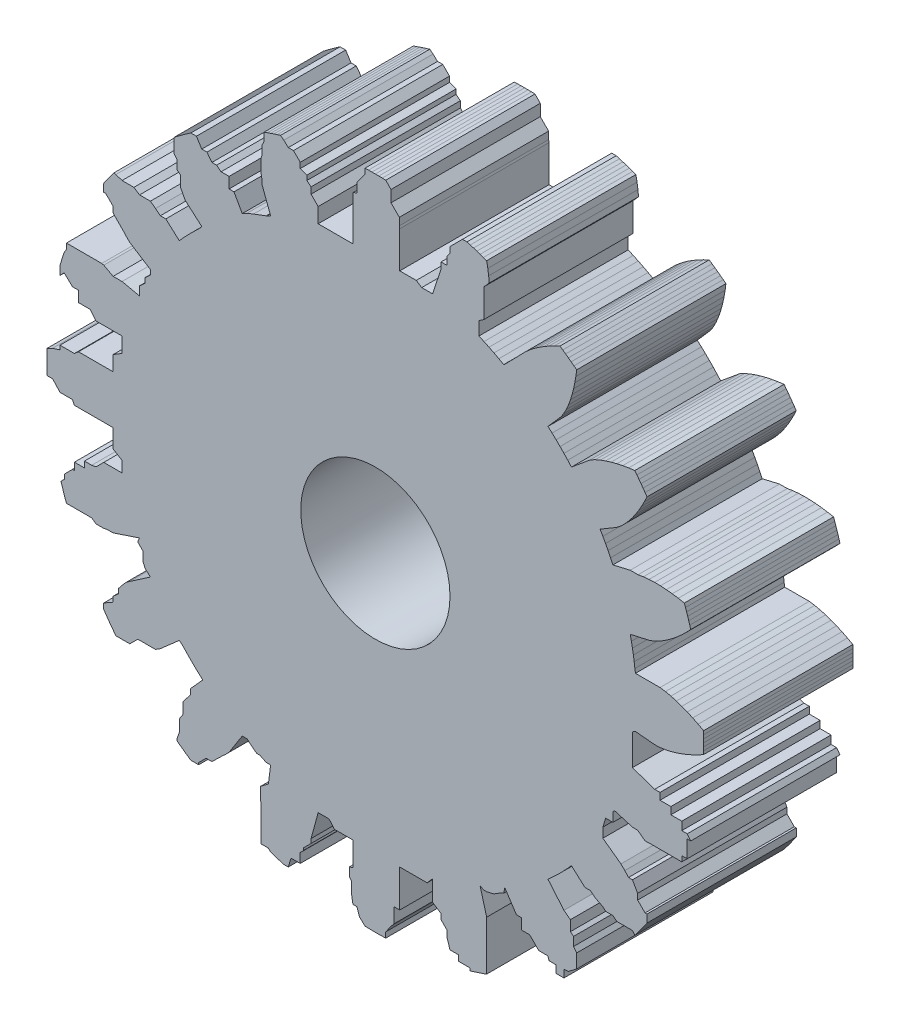
SolidWorks part; units mm, degrees
ref_plane "前视基准面" through (0, 0, 0) normal (0, 0, 1) x (1, 0, 0)
ref_plane "上视基准面" through (0, 0, 0) normal (0, 1, 0) x (1, 0, 0)
ref_plane "右视基准面" through (0, 0, 0) normal (1, 0, 0) x (0, 0, -1)
other "Configuration Table"
sketch "草图1" plane through (0, 0, 0) normal (0, 0, 1) x (1, 0, 0)
  line L0 (17.4237, -1.6329) -> (18.7119, -1.7536)
  line L1 (18.7119, -1.7536) -> (19.0708, -1.7403)
  line L2 (19.0708, -1.7403) -> (19.4332, -1.6872)
  line L3 (19.4332, -1.6872) -> (19.7975, -1.6066)
  line L4 (19.7975, -1.6066) -> (20.1629, -1.5029)
  line L5 (20.1629, -1.5029) -> (20.5288, -1.3783)
  line L6 (20.5288, -1.3783) -> (20.8949, -1.2343)
  line L7 (20.8949, -1.2343) -> (21.2605, -1.0719)
  line L8 (21.2605, -1.0719) -> (21.6254, -0.8918)
  line L9 (21.6254, -0.8918) -> (21.989, -0.6948)
  line L10 (21.989, -0.6948) -> (21.9951, -0.4632)
  line L11 (21.9951, -0.4632) -> (21.9988, -0.2316)
  line L12 (21.9988, -0.2316) -> (22, 0)
  line L13 (22, 0) -> (21.9988, 0.2316)
  line L14 (21.9988, 0.2316) -> (21.9951, 0.4632)
  line L15 (21.9951, 0.4632) -> (21.989, 0.6948)
  line L16 (21.989, 0.6948) -> (21.6254, 0.8918)
  line L17 (21.6254, 0.8918) -> (21.2605, 1.0719)
  line L18 (21.2605, 1.0719) -> (20.8949, 1.2343)
  line L19 (20.8949, 1.2343) -> (20.5288, 1.3783)
  line L20 (20.5288, 1.3783) -> (20.1629, 1.5029)
  line L21 (20.1629, 1.5029) -> (19.7975, 1.6066)
  line L22 (19.7975, 1.6066) -> (19.4332, 1.6872)
  line L23 (19.4332, 1.6872) -> (19.0708, 1.7403)
  line L24 (19.0708, 1.7403) -> (17.4237, 1.7403)
  line L25 (17.4237, 1.7403) -> (17.3851, 2.0021)
  line L26 (17.3851, 2.0021) -> (17.3387, 2.3704)
  line L27 (17.3387, 2.3704) -> (17.2845, 2.7376)
  line L28 (17.2845, 2.7376) -> (17.2226, 3.1036)
  line L29 (17.2226, 3.1036) -> (17.1529, 3.4682)
  line L30 (17.1529, 3.4682) -> (17.0755, 3.8312)
  line L31 (17.0755, 3.8312) -> (18.3379, 4.1145)
  line L32 (18.3379, 4.1145) -> (18.6752, 4.2381)
  line L33 (18.6752, 4.2381) -> (19.0035, 4.4006)
  line L34 (19.0035, 4.4006) -> (19.325, 4.5898)
  line L35 (19.325, 4.5898) -> (19.6404, 4.8013)
  line L36 (19.6404, 4.8013) -> (19.95, 5.0329)
  line L37 (19.95, 5.0329) -> (20.2536, 5.283)
  line L38 (20.2536, 5.283) -> (20.5512, 5.5505)
  line L39 (20.5512, 5.5505) -> (20.8425, 5.8344)
  line L40 (20.8425, 5.8344) -> (21.1275, 6.1342)
  line L41 (21.1275, 6.1342) -> (21.0617, 6.3563)
  line L42 (21.0617, 6.3563) -> (20.9937, 6.5777)
  line L43 (20.9937, 6.5777) -> (20.9232, 6.7984)
  line L44 (20.9232, 6.7984) -> (20.8505, 7.0183)
  line L45 (20.8505, 7.0183) -> (20.7755, 7.2374)
  line L46 (20.7755, 7.2374) -> (20.6981, 7.4557)
  line L47 (20.6981, 7.4557) -> (20.2914, 7.5308)
  line L48 (20.2914, 7.5308) -> (19.8887, 7.5893)
  line L49 (19.8887, 7.5893) -> (19.4908, 7.6307)
  line L50 (19.4908, 7.6307) -> (19.0982, 7.6546)
  line L51 (19.0982, 7.6546) -> (18.7116, 7.66)
  line L52 (18.7116, 7.66) -> (18.3321, 7.6457)
  line L53 (18.3321, 7.6457) -> (17.9607, 7.6098)
  line L54 (17.9607, 7.6098) -> (17.5997, 7.5484)
  line L55 (17.5997, 7.5484) -> (17.0755, 7.5484)
  line L56 (17.0755, 7.5484) -> (15.9155, 7.2764)
  line L57 (15.9155, 7.2764) -> (15.7576, 7.6123)
  line L58 (15.7576, 7.6123) -> (15.5926, 7.9448)
  line L59 (15.5926, 7.9448) -> (15.4206, 8.2738)
  line L60 (15.4206, 8.2738) -> (15.2416, 8.599)
  line L61 (15.2416, 8.599) -> (15.0558, 8.9203)
  line L62 (15.0558, 8.9203) -> (16.169, 9.5798)
  line L63 (16.169, 9.5798) -> (16.4516, 9.8016)
  line L64 (16.4516, 9.8016) -> (16.7135, 10.0576)
  line L65 (16.7135, 10.0576) -> (16.9608, 10.3369)
  line L66 (16.9608, 10.3369) -> (17.1955, 10.6356)
  line L67 (17.1955, 10.6356) -> (17.4183, 10.9515)
  line L68 (17.4183, 10.9515) -> (17.6298, 11.2832)
  line L69 (17.6298, 11.2832) -> (17.8301, 11.6295)
  line L70 (17.8301, 11.6295) -> (18.0195, 11.9896)
  line L71 (18.0195, 11.9896) -> (18.1979, 12.3627)
  line L72 (18.1979, 12.3627) -> (18.0667, 12.5537)
  line L73 (18.0667, 12.5537) -> (17.9335, 12.7432)
  line L74 (17.9335, 12.7432) -> (17.7984, 12.9313)
  line L75 (17.7984, 12.9313) -> (17.6612, 13.1179)
  line L76 (17.6612, 13.1179) -> (17.5222, 13.3032)
  line L77 (17.5222, 13.3032) -> (17.3811, 13.4869)
  line L78 (17.3811, 13.4869) -> (16.9711, 13.4326)
  line L79 (16.9711, 13.4326) -> (16.5701, 13.3638)
  line L80 (16.5701, 13.3638) -> (16.1788, 13.2802)
  line L81 (16.1788, 13.2802) -> (15.798, 13.1816)
  line L82 (15.798, 13.1816) -> (15.4287, 13.0673)
  line L83 (15.4287, 13.0673) -> (15.0722, 12.9364)
  line L84 (15.0722, 12.9364) -> (14.7301, 12.7875)
  line L85 (14.7301, 12.7875) -> (14.4057, 12.6175)
  line L86 (14.4057, 12.6175) -> (13.1362, 11.5624)
  line L87 (13.1362, 11.5624) -> (12.888, 11.8384)
  line L88 (12.888, 11.8384) -> (12.634, 12.1091)
  line L89 (12.634, 12.1091) -> (12.3744, 12.3744)
  line L90 (12.3744, 12.3744) -> (12.1091, 12.634)
  line L91 (12.1091, 12.634) -> (11.8384, 12.888)
  line L92 (11.8384, 12.888) -> (11.5624, 13.1362)
  line L93 (11.5624, 13.1362) -> (12.4173, 14.1075)
  line L94 (12.4173, 14.1075) -> (12.6175, 14.4057)
  line L95 (12.6175, 14.4057) -> (12.7875, 14.7301)
  line L96 (12.7875, 14.7301) -> (12.9364, 15.0722)
  line L97 (12.9364, 15.0722) -> (13.0673, 15.4287)
  line L98 (13.0673, 15.4287) -> (13.1816, 15.798)
  line L99 (13.1816, 15.798) -> (13.2802, 16.1788)
  line L100 (13.2802, 16.1788) -> (13.3638, 16.5701)
  line L101 (13.3638, 16.5701) -> (13.4326, 16.9711)
  line L102 (13.4326, 16.9711) -> (13.4869, 17.3811)
  line L103 (13.4869, 17.3811) -> (13.3032, 17.5222)
  line L104 (13.3032, 17.5222) -> (13.1179, 17.6612)
  line L105 (13.1179, 17.6612) -> (12.9313, 17.7984)
  line L106 (12.9313, 17.7984) -> (12.7432, 17.9335)
  line L107 (12.7432, 17.9335) -> (12.5537, 18.0667)
  line L108 (12.5537, 18.0667) -> (12.3627, 18.1979)
  line L109 (12.3627, 18.1979) -> (11.9896, 18.0195)
  line L110 (11.9896, 18.0195) -> (11.6295, 17.8301)
  line L111 (11.6295, 17.8301) -> (11.2832, 17.6298)
  line L112 (11.2832, 17.6298) -> (10.9515, 17.4183)
  line L113 (10.9515, 17.4183) -> (10.6356, 17.1955)
  line L114 (10.6356, 17.1955) -> (10.3369, 16.9608)
  line L115 (10.3369, 16.9608) -> (10.0576, 16.7135)
  line L116 (10.0576, 16.7135) -> (9.8016, 16.4516)
  line L117 (9.8016, 16.4516) -> (8.6733, 15.2973)
  line L118 (8.6733, 15.2973) -> (8.599, 15.2416)
  line L119 (8.599, 15.2416) -> (8.2738, 15.4206)
  line L120 (8.2738, 15.4206) -> (7.9448, 15.5926)
  line L121 (7.9448, 15.5926) -> (7.6123, 15.7576)
  line L122 (7.6123, 15.7576) -> (7.2764, 15.9155)
  line L123 (7.2764, 15.9155) -> (6.9372, 16.0663)
  line L124 (6.9372, 16.0663) -> (6.9372, 16.9608)
  line L125 (6.9372, 16.9608) -> (7.2764, 17.1955)
  line L126 (7.2764, 17.1955) -> (7.2764, 17.6298)
  line L127 (7.2764, 17.6298) -> (7.2764, 17.8301)
  line L128 (7.2764, 17.8301) -> (7.2764, 18.1979)
  line L129 (7.2764, 18.1979) -> (7.2764, 19.0982)
  line L130 (7.2764, 19.0982) -> (7.6307, 19.4908)
  line L131 (7.6307, 19.4908) -> (7.5893, 19.8887)
  line L132 (7.5893, 19.8887) -> (7.5308, 20.2914)
  line L133 (7.5308, 20.2914) -> (7.4557, 20.6981)
  line L134 (7.4557, 20.6981) -> (7.2374, 20.7755)
  line L135 (7.2374, 20.7755) -> (7.0183, 20.8505)
  line L136 (7.0183, 20.8505) -> (6.7984, 20.9232)
  line L137 (6.7984, 20.9232) -> (6.5777, 20.9937)
  line L138 (6.5777, 20.9937) -> (6.3563, 21.0617)
  line L139 (6.3563, 21.0617) -> (6.1342, 21.1275)
  line L140 (6.1342, 21.1275) -> (5.8344, 21.1275)
  line L141 (5.8344, 21.1275) -> (5.5574, 20.8505)
  line L142 (5.5574, 20.8505) -> (4.9983, 20.2914)
  line L143 (4.9983, 20.2914) -> (4.9983, 19.8887)
  line L144 (4.9983, 19.8887) -> (4.8013, 19.6404)
  line L145 (4.8013, 19.6404) -> (4.8013, 19.0982)
  line L146 (4.8013, 19.0982) -> (4.4006, 19.0982)
  line L147 (4.4006, 19.0982) -> (4.4006, 18.6752)
  line L148 (4.4006, 18.6752) -> (3.8312, 16.9608)
  line L149 (3.8312, 16.9608) -> (3.4682, 16.9608)
  line L150 (3.4682, 16.9608) -> (3.1036, 16.9608)
  line L151 (3.1036, 16.9608) -> (2.7376, 17.1955)
  line L152 (2.7376, 17.1955) -> (2.3704, 17.1955)
  line L153 (2.3704, 17.1955) -> (2.0021, 17.1955)
  line L154 (2.0021, 17.1955) -> (1.6329, 17.1955)
  line L155 (1.6329, 17.1955) -> (1.6329, 18.6752)
  line L156 (1.6329, 18.6752) -> (1.6329, 19.0982)
  line L157 (1.6329, 19.0982) -> (1.6329, 19.6404)
  line L158 (1.6329, 19.6404) -> (1.6066, 19.7975)
  line L159 (1.6066, 19.7975) -> (1.6066, 19.8887)
  line L160 (1.6066, 19.8887) -> (1.6066, 20.2914)
  line L161 (1.6066, 20.2914) -> (1.0475, 20.8505)
  line L162 (1.0475, 20.8505) -> (1.0475, 21.1275)
  line L163 (1.0475, 21.1275) -> (1.0475, 21.6254)
  line L164 (1.0475, 21.6254) -> (0.6948, 21.989)
  line L165 (0.6948, 21.989) -> (0.4632, 21.9951)
  line L166 (0.4632, 21.9951) -> (0.2316, 21.9988)
  line L167 (0.2316, 21.9988) -> (0, 22)
  line L168 (0, 22) -> (-0.2316, 21.9988)
  line L169 (-0.2316, 21.9988) -> (-0.4632, 21.9951)
  line L170 (-0.4632, 21.9951) -> (-0.6948, 21.989)
  line L171 (-0.6948, 21.989) -> (-0.6948, 21.6254)
  line L172 (-0.6948, 21.6254) -> (-1.0719, 21.1275)
  line L173 (-1.0719, 21.1275) -> (-1.2343, 20.8949)
  line L174 (-1.2343, 20.8949) -> (-1.2343, 20.2914)
  line L175 (-1.2343, 20.2914) -> (-1.5029, 20.1629)
  line L176 (-1.5029, 20.1629) -> (-1.5029, 19.7975)
  line L177 (-1.5029, 19.7975) -> (-1.5029, 19.6404)
  line L178 (-1.5029, 19.6404) -> (-1.5029, 19.0982)
  line L179 (-1.5029, 19.0982) -> (-1.5029, 17.1955)
  line L180 (-1.5029, 17.1955) -> (-2.0021, 17.1955)
  line L181 (-2.0021, 17.1955) -> (-2.3704, 17.1955)
  line L182 (-2.3704, 17.1955) -> (-2.7376, 17.1955)
  line L183 (-2.7376, 17.1955) -> (-3.1036, 17.1955)
  line L184 (-3.1036, 17.1955) -> (-3.4682, 17.1955)
  line L185 (-3.4682, 17.1955) -> (-3.8312, 17.1955)
  line L186 (-3.8312, 17.1955) -> (-3.8312, 18.1979)
  line L187 (-3.8312, 18.1979) -> (-4.3086, 18.6752)
  line L188 (-4.3086, 18.6752) -> (-4.3086, 19.0982)
  line L189 (-4.3086, 19.0982) -> (-4.5898, 19.325)
  line L190 (-4.5898, 19.325) -> (-4.5898, 19.6404)
  line L191 (-4.5898, 19.6404) -> (-5.0329, 19.7975)
  line L192 (-5.0329, 19.7975) -> (-5.0329, 20.1629)
  line L193 (-5.0329, 20.1629) -> (-5.4859, 20.6158)
  line L194 (-5.4859, 20.6158) -> (-5.8344, 20.6158)
  line L195 (-5.8344, 20.6158) -> (-6.1342, 20.8949)
  line L196 (-6.1342, 20.8949) -> (-6.3563, 21.0617)
  line L197 (-6.3563, 21.0617) -> (-6.5777, 20.9937)
  line L198 (-6.5777, 20.9937) -> (-6.7984, 20.9232)
  line L199 (-6.7984, 20.9232) -> (-7.0183, 20.8505)
  line L200 (-7.0183, 20.8505) -> (-7.2374, 20.7755)
  line L201 (-7.2374, 20.7755) -> (-7.4557, 20.6981)
  line L202 (-7.4557, 20.6981) -> (-7.4557, 20.1629)
  line L203 (-7.4557, 20.1629) -> (-7.5893, 19.8887)
  line L204 (-7.5893, 19.8887) -> (-7.5893, 19.325)
  line L205 (-7.5893, 19.325) -> (-7.6546, 19.0982)
  line L206 (-7.6546, 19.0982) -> (-7.6546, 18.6752)
  line L207 (-7.6546, 18.6752) -> (-7.6546, 18.1979)
  line L208 (-7.6546, 18.1979) -> (-7.6098, 17.9607)
  line L209 (-7.6098, 17.9607) -> (-7.6098, 17.6298)
  line L210 (-7.6098, 17.6298) -> (-7.0183, 16.0663)
  line L211 (-7.0183, 16.0663) -> (-7.2764, 15.9155)
  line L212 (-7.2764, 15.9155) -> (-7.314, 15.9155)
  line L213 (-7.314, 15.9155) -> (-7.7314, 15.7576)
  line L214 (-7.7314, 15.7576) -> (-8.1676, 15.5926)
  line L215 (-8.1676, 15.5926) -> (-8.599, 15.4206)
  line L216 (-8.599, 15.4206) -> (-8.9203, 15.2416)
  line L217 (-8.9203, 15.2416) -> (-9.4706, 16.2298)
  line L218 (-9.4706, 16.2298) -> (-9.8016, 16.2298)
  line L219 (-9.8016, 16.2298) -> (-9.8016, 16.9608)
  line L220 (-9.8016, 16.9608) -> (-10.3369, 16.9608)
  line L221 (-10.3369, 16.9608) -> (-10.6356, 17.1955)
  line L222 (-10.6356, 17.1955) -> (-10.9515, 17.1955)
  line L223 (-10.9515, 17.1955) -> (-11.2832, 17.6298)
  line L224 (-11.2832, 17.6298) -> (-11.6295, 17.6298)
  line L225 (-11.6295, 17.6298) -> (-11.9896, 18.1979)
  line L226 (-11.9896, 18.1979) -> (-12.3627, 18.1979)
  line L227 (-12.3627, 18.1979) -> (-12.5537, 18.0667)
  line L228 (-12.5537, 18.0667) -> (-12.7432, 17.9335)
  line L229 (-12.7432, 17.9335) -> (-12.9313, 17.7984)
  line L230 (-12.9313, 17.7984) -> (-13.1179, 17.6612)
  line L231 (-13.1179, 17.6612) -> (-13.3032, 17.5222)
  line L232 (-13.3032, 17.5222) -> (-13.4869, 17.3811)
  line L233 (-13.4869, 17.3811) -> (-13.4869, 17.1955)
  line L234 (-13.4869, 17.1955) -> (-13.4869, 16.4516)
  line L235 (-13.4869, 16.4516) -> (-13.2802, 16.1788)
  line L236 (-13.2802, 16.1788) -> (-13.2802, 15.5926)
  line L237 (-13.2802, 15.5926) -> (-13.0673, 15.4287)
  line L238 (-13.0673, 15.4287) -> (-13.0673, 15.2416)
  line L239 (-13.0673, 15.2416) -> (-13.0673, 14.7301)
  line L240 (-13.0673, 14.7301) -> (-12.7432, 14.1075)
  line L241 (-12.7432, 14.1075) -> (-11.6295, 13.1362)
  line L242 (-11.6295, 13.1362) -> (-11.8384, 12.888)
  line L243 (-11.8384, 12.888) -> (-12.1091, 12.634)
  line L244 (-12.1091, 12.634) -> (-12.3744, 12.3744)
  line L245 (-12.3744, 12.3744) -> (-12.634, 12.1091)
  line L246 (-12.634, 12.1091) -> (-12.888, 11.8384)
  line L247 (-12.888, 11.8384) -> (-13.1362, 11.5624)
  line L248 (-13.1362, 11.5624) -> (-14.0392, 12.3744)
  line L249 (-14.0392, 12.3744) -> (-14.4057, 12.3744)
  line L250 (-14.4057, 12.3744) -> (-14.7301, 12.634)
  line L251 (-14.7301, 12.634) -> (-15.0722, 12.888)
  line L252 (-15.0722, 12.888) -> (-15.4287, 12.888)
  line L253 (-15.4287, 12.888) -> (-15.798, 12.888)
  line L254 (-15.798, 12.888) -> (-16.1788, 13.1362)
  line L255 (-16.1788, 13.1362) -> (-16.5701, 13.1362)
  line L256 (-16.5701, 13.1362) -> (-16.9711, 13.1362)
  line L257 (-16.9711, 13.1362) -> (-17.3811, 13.2802)
  line L258 (-17.3811, 13.2802) -> (-17.5222, 13.3032)
  line L259 (-17.5222, 13.3032) -> (-17.6612, 13.1179)
  line L260 (-17.6612, 13.1179) -> (-17.7984, 12.9313)
  line L261 (-17.7984, 12.9313) -> (-17.9335, 12.7432)
  line L262 (-17.9335, 12.7432) -> (-18.0667, 12.5537)
  line L263 (-18.0667, 12.5537) -> (-18.1979, 12.3627)
  line L264 (-18.1979, 12.3627) -> (-18.1979, 11.8384)
  line L265 (-18.1979, 11.8384) -> (-18.0667, 11.8384)
  line L266 (-18.0667, 11.8384) -> (-17.5706, 11.3423)
  line L267 (-17.5706, 11.3423) -> (-17.5706, 10.9515)
  line L268 (-17.5706, 10.9515) -> (-16.9711, 10.3369)
  line L269 (-16.9711, 10.3369) -> (-16.9608, 10.3369)
  line L270 (-16.9608, 10.3369) -> (-16.7135, 10.0576)
  line L271 (-16.7135, 10.0576) -> (-16.4516, 9.8016)
  line L272 (-16.4516, 9.8016) -> (-15.0722, 8.9203)
  line L273 (-15.0722, 8.9203) -> (-15.0722, 8.599)
  line L274 (-15.0722, 8.599) -> (-15.4287, 8.2738)
  line L275 (-15.4287, 8.2738) -> (-15.4287, 7.9448)
  line L276 (-15.4287, 7.9448) -> (-15.798, 7.6123)
  line L277 (-15.798, 7.6123) -> (-15.798, 7.2764)
  line L278 (-15.798, 7.2764) -> (-15.798, 7.0183)
  line L279 (-15.798, 7.0183) -> (-16.9711, 7.2764)
  line L280 (-16.9711, 7.2764) -> (-17.5706, 7.2764)
  line L281 (-17.5706, 7.2764) -> (-18.1979, 7.6123)
  line L282 (-18.1979, 7.6123) -> (-18.3321, 7.6457)
  line L283 (-18.3321, 7.6457) -> (-18.7116, 7.6457)
  line L284 (-18.7116, 7.6457) -> (-19.0982, 7.6457)
  line L285 (-19.0982, 7.6457) -> (-19.4908, 7.6457)
  line L286 (-19.4908, 7.6457) -> (-19.8887, 7.6457)
  line L287 (-19.8887, 7.6457) -> (-20.2914, 7.6457)
  line L288 (-20.2914, 7.6457) -> (-20.6981, 7.6457)
  line L289 (-20.6981, 7.6457) -> (-20.6981, 7.2764)
  line L290 (-20.6981, 7.2764) -> (-20.8505, 7.0183)
  line L291 (-20.8505, 7.0183) -> (-20.9232, 6.7984)
  line L292 (-20.9232, 6.7984) -> (-20.9937, 6.5777)
  line L293 (-20.9937, 6.5777) -> (-21.0617, 6.3563)
  line L294 (-21.0617, 6.3563) -> (-21.1275, 6.1342)
  line L295 (-21.1275, 6.1342) -> (-21.1275, 5.5505)
  line L296 (-21.1275, 5.5505) -> (-20.8505, 5.8423)
  line L297 (-20.8505, 5.8423) -> (-20.2914, 5.3117)
  line L298 (-20.2914, 5.3117) -> (-19.8887, 5.3117)
  line L299 (-19.8887, 5.3117) -> (-19.8887, 4.5898)
  line L300 (-19.8887, 4.5898) -> (-19.4908, 4.5898)
  line L301 (-19.4908, 4.5898) -> (-19.0982, 4.5898)
  line L302 (-19.0982, 4.5898) -> (-18.7116, 4.1145)
  line L303 (-18.7116, 4.1145) -> (-16.9711, 4.1145)
  line L304 (-16.9711, 4.1145) -> (-16.9711, 3.4682)
  line L305 (-16.9711, 3.4682) -> (-16.9711, 3.1036)
  line L306 (-16.9711, 3.1036) -> (-17.5706, 2.7376)
  line L307 (-17.5706, 2.7376) -> (-17.5706, 2.3704)
  line L308 (-17.5706, 2.3704) -> (-17.5706, 2.0021)
  line L309 (-17.5706, 2.0021) -> (-17.5706, 1.7403)
  line L310 (-17.5706, 1.7403) -> (-18.7116, 1.7403)
  line L311 (-18.7116, 1.7403) -> (-19.0982, 1.7403)
  line L312 (-19.0982, 1.7403) -> (-19.4908, 1.7403)
  line L313 (-19.4908, 1.7403) -> (-19.8887, 1.7403)
  line L314 (-19.8887, 1.7403) -> (-20.1629, 1.5029)
  line L315 (-20.1629, 1.5029) -> (-20.2914, 1.5029)
  line L316 (-20.2914, 1.5029) -> (-21.1275, 1.5029)
  line L317 (-21.1275, 1.5029) -> (-21.1275, 1.2343)
  line L318 (-21.1275, 1.2343) -> (-21.6254, 1.0719)
  line L319 (-21.6254, 1.0719) -> (-21.989, 0.8918)
  line L320 (-21.989, 0.8918) -> (-21.989, 0.6948)
  line L321 (-21.989, 0.6948) -> (-21.989, 0)
  line L322 (-21.989, 0) -> (-22, 0)
  line L323 (-22, 0) -> (-21.9988, -0.2316)
  line L324 (-21.9988, -0.2316) -> (-21.9951, -0.4632)
  line L325 (-21.9951, -0.4632) -> (-21.989, -0.6948)
  line L326 (-21.989, -0.6948) -> (-21.6254, -0.6948)
  line L327 (-21.6254, -0.6948) -> (-21.1275, -1.2343)
  line L328 (-21.1275, -1.2343) -> (-20.8949, -1.2343)
  line L329 (-20.8949, -1.2343) -> (-20.2914, -1.2343)
  line L330 (-20.2914, -1.2343) -> (-20.1629, -1.5029)
  line L331 (-20.1629, -1.5029) -> (-19.8887, -1.5029)
  line L332 (-19.8887, -1.5029) -> (-19.4908, -1.5029)
  line L333 (-19.4908, -1.5029) -> (-19.0982, -1.5029)
  line L334 (-19.0982, -1.5029) -> (-17.5706, -1.5029)
  line L335 (-17.5706, -1.5029) -> (-17.5706, -1.7536)
  line L336 (-17.5706, -1.7536) -> (-17.5706, -2.3704)
  line L337 (-17.5706, -2.3704) -> (-17.5706, -2.7376)
  line L338 (-17.5706, -2.7376) -> (-16.9711, -3.1036)
  line L339 (-16.9711, -3.1036) -> (-16.9711, -3.4682)
  line L340 (-16.9711, -3.4682) -> (-16.9711, -3.8312)
  line L341 (-16.9711, -3.8312) -> (-18.1979, -3.8312)
  line L342 (-18.1979, -3.8312) -> (-18.7116, -4.345)
  line L343 (-18.7116, -4.345) -> (-19.0035, -4.4006)
  line L344 (-19.0035, -4.4006) -> (-19.4908, -4.4006)
  line L345 (-19.4908, -4.4006) -> (-19.4908, -4.8013)
  line L346 (-19.4908, -4.8013) -> (-20.1629, -4.8013)
  line L347 (-20.1629, -4.8013) -> (-20.1629, -5.283)
  line L348 (-20.1629, -5.283) -> (-20.2914, -5.283)
  line L349 (-20.2914, -5.283) -> (-20.8427, -5.8343)
  line L350 (-20.8427, -5.8343) -> (-20.8427, -6.1342)
  line L351 (-20.8427, -6.1342) -> (-21.0617, -6.3563)
  line L352 (-21.0617, -6.3563) -> (-20.9937, -6.5777)
  line L353 (-20.9937, -6.5777) -> (-20.9232, -6.7984)
  line L354 (-20.9232, -6.7984) -> (-20.8505, -7.0183)
  line L355 (-20.8505, -7.0183) -> (-20.7755, -7.2374)
  line L356 (-20.7755, -7.2374) -> (-20.6981, -7.4557)
  line L357 (-20.6981, -7.4557) -> (-20.2914, -7.4557)
  line L358 (-20.2914, -7.4557) -> (-20.1629, -7.4557)
  line L359 (-20.1629, -7.4557) -> (-19.4908, -7.4557)
  line L360 (-19.4908, -7.4557) -> (-19.0035, -7.4557)
  line L361 (-19.0035, -7.4557) -> (-18.7116, -7.66)
  line L362 (-18.7116, -7.66) -> (-18.1979, -7.66)
  line L363 (-18.1979, -7.66) -> (-17.9607, -7.6098)
  line L364 (-17.9607, -7.6098) -> (-17.5706, -7.6098)
  line L365 (-17.5706, -7.6098) -> (-15.798, -7.0183)
  line L366 (-15.798, -7.0183) -> (-15.9155, -7.2764)
  line L367 (-15.9155, -7.2764) -> (-15.9155, -7.314)
  line L368 (-15.9155, -7.314) -> (-15.5696, -7.66)
  line L369 (-15.5696, -7.66) -> (-15.5696, -8.2738)
  line L370 (-15.5696, -8.2738) -> (-15.4287, -8.599)
  line L371 (-15.4287, -8.599) -> (-15.0722, -8.9203)
  line L372 (-15.0722, -8.9203) -> (-15.9155, -9.4976)
  line L373 (-15.9155, -9.4976) -> (-16.4516, -9.8646)
  line L374 (-16.4516, -9.8646) -> (-16.7135, -10.0576)
  line L375 (-16.7135, -10.0576) -> (-16.9608, -10.3369)
  line L376 (-16.9608, -10.3369) -> (-17.1955, -10.6356)
  line L377 (-17.1955, -10.6356) -> (-17.1955, -10.9515)
  line L378 (-17.1955, -10.9515) -> (-17.5706, -11.2832)
  line L379 (-17.5706, -11.2832) -> (-17.5706, -11.6295)
  line L380 (-17.5706, -11.6295) -> (-18.1979, -11.9896)
  line L381 (-18.1979, -11.9896) -> (-18.1979, -12.3627)
  line L382 (-18.1979, -12.3627) -> (-18.0667, -12.5537)
  line L383 (-18.0667, -12.5537) -> (-17.9335, -12.7432)
  line L384 (-17.9335, -12.7432) -> (-17.7984, -12.9313)
  line L385 (-17.7984, -12.9313) -> (-17.6612, -13.1179)
  line L386 (-17.6612, -13.1179) -> (-17.5222, -13.3032)
  line L387 (-17.5222, -13.3032) -> (-17.3811, -13.4869)
  line L388 (-17.3811, -13.4869) -> (-17.1955, -13.4869)
  line L389 (-17.1955, -13.4869) -> (-16.7135, -13.4869)
  line L390 (-16.7135, -13.4869) -> (-16.4516, -13.4869)
  line L391 (-16.4516, -13.4869) -> (-15.9155, -12.9508)
  line L392 (-15.9155, -12.9508) -> (-15.4287, -12.9508)
  line L393 (-15.4287, -12.9508) -> (-15.0722, -12.9508)
  line L394 (-15.0722, -12.9508) -> (-14.7301, -12.9508)
  line L395 (-14.7301, -12.9508) -> (-14.4057, -12.7432)
  line L396 (-14.4057, -12.7432) -> (-13.1362, -11.6295)
  line L397 (-13.1362, -11.6295) -> (-12.888, -11.8384)
  line L398 (-12.888, -11.8384) -> (-12.634, -12.1091)
  line L399 (-12.634, -12.1091) -> (-12.3744, -12.3744)
  line L400 (-12.3744, -12.3744) -> (-12.1091, -12.634)
  line L401 (-12.1091, -12.634) -> (-11.8384, -12.888)
  line L402 (-11.8384, -12.888) -> (-11.5624, -13.1362)
  line L403 (-11.5624, -13.1362) -> (-12.3744, -14.0392)
  line L404 (-12.3744, -14.0392) -> (-12.3744, -14.4057)
  line L405 (-12.3744, -14.4057) -> (-12.634, -14.7301)
  line L406 (-12.634, -14.7301) -> (-12.888, -15.0722)
  line L407 (-12.888, -15.0722) -> (-12.888, -15.4287)
  line L408 (-12.888, -15.4287) -> (-12.888, -15.798)
  line L409 (-12.888, -15.798) -> (-13.1362, -16.1788)
  line L410 (-13.1362, -16.1788) -> (-13.1362, -16.5701)
  line L411 (-13.1362, -16.5701) -> (-13.1362, -16.9711)
  line L412 (-13.1362, -16.9711) -> (-13.2802, -17.3811)
  line L413 (-13.2802, -17.3811) -> (-13.3032, -17.5222)
  line L414 (-13.3032, -17.5222) -> (-13.1179, -17.6612)
  line L415 (-13.1179, -17.6612) -> (-12.9313, -17.7984)
  line L416 (-12.9313, -17.7984) -> (-12.7432, -17.9335)
  line L417 (-12.7432, -17.9335) -> (-12.5537, -18.0667)
  line L418 (-12.5537, -18.0667) -> (-12.3627, -18.1979)
  line L419 (-12.3627, -18.1979) -> (-11.8384, -18.1979)
  line L420 (-11.8384, -18.1979) -> (-11.8384, -18.0667)
  line L421 (-11.8384, -18.0667) -> (-11.3423, -17.5706)
  line L422 (-11.3423, -17.5706) -> (-10.9515, -17.5706)
  line L423 (-10.9515, -17.5706) -> (-10.3369, -16.9711)
  line L424 (-10.3369, -16.9711) -> (-10.3369, -16.9608)
  line L425 (-10.3369, -16.9608) -> (-10.0576, -16.7135)
  line L426 (-10.0576, -16.7135) -> (-9.8016, -16.4516)
  line L427 (-9.8016, -16.4516) -> (-8.9203, -15.0722)
  line L428 (-8.9203, -15.0722) -> (-8.599, -15.0722)
  line L429 (-8.599, -15.0722) -> (-8.1676, -15.4287)
  line L430 (-8.1676, -15.4287) -> (-7.9448, -15.5926)
  line L431 (-7.9448, -15.5926) -> (-7.7314, -15.5926)
  line L432 (-7.7314, -15.5926) -> (-7.314, -15.798)
  line L433 (-7.314, -15.798) -> (-7.0183, -15.798)
  line L434 (-7.0183, -15.798) -> (-7.1662, -16.9711)
  line L435 (-7.1662, -16.9711) -> (-7.7091, -17.3925)
  line L436 (-7.7091, -17.3925) -> (-7.7091, -18.1979)
  line L437 (-7.7091, -18.1979) -> (-7.6457, -18.3321)
  line L438 (-7.6457, -18.3321) -> (-7.6457, -18.7116)
  line L439 (-7.6457, -18.7116) -> (-7.6457, -19.0982)
  line L440 (-7.6457, -19.0982) -> (-7.6457, -19.4908)
  line L441 (-7.6457, -19.4908) -> (-7.6457, -19.8887)
  line L442 (-7.6457, -19.8887) -> (-7.6457, -20.2914)
  line L443 (-7.6457, -20.2914) -> (-7.6457, -20.6981)
  line L444 (-7.6457, -20.6981) -> (-7.1662, -20.6981)
  line L445 (-7.1662, -20.6981) -> (-7.0183, -20.8505)
  line L446 (-7.0183, -20.8505) -> (-6.7984, -20.9232)
  line L447 (-6.7984, -20.9232) -> (-6.5777, -20.9937)
  line L448 (-6.5777, -20.9937) -> (-6.3563, -21.0617)
  line L449 (-6.3563, -21.0617) -> (-6.1342, -21.1275)
  line L450 (-6.1342, -21.1275) -> (-5.8344, -21.1275)
  line L451 (-5.8344, -21.1275) -> (-5.6547, -20.5203)
  line L452 (-5.6547, -20.5203) -> (-5.0329, -20.5203)
  line L453 (-5.0329, -20.5203) -> (-5.0329, -19.8887)
  line L454 (-5.0329, -19.8887) -> (-4.8013, -19.6404)
  line L455 (-4.8013, -19.6404) -> (-4.8013, -19.4908)
  line L456 (-4.8013, -19.4908) -> (-4.3086, -18.998)
  line L457 (-4.3086, -18.998) -> (-4.3086, -18.7116)
  line L458 (-4.3086, -18.7116) -> (-3.8312, -16.9711)
  line L459 (-3.8312, -16.9711) -> (-3.4682, -16.9711)
  line L460 (-3.4682, -16.9711) -> (-3.1036, -16.9711)
  line L461 (-3.1036, -16.9711) -> (-2.7376, -17.3925)
  line L462 (-2.7376, -17.3925) -> (-2.3704, -17.3925)
  line L463 (-2.3704, -17.3925) -> (-2.0021, -17.3925)
  line L464 (-2.0021, -17.3925) -> (-1.5029, -17.3925)
  line L465 (-1.5029, -17.3925) -> (-1.5029, -18.998)
  line L466 (-1.5029, -18.998) -> (-1.7403, -19.0708)
  line L467 (-1.7403, -19.0708) -> (-1.7403, -19.6404)
  line L468 (-1.7403, -19.6404) -> (-1.6066, -19.7975)
  line L469 (-1.6066, -19.7975) -> (-1.6066, -19.8887)
  line L470 (-1.6066, -19.8887) -> (-1.6066, -20.5203)
  line L471 (-1.6066, -20.5203) -> (-1.5029, -21.1275)
  line L472 (-1.5029, -21.1275) -> (-1.2343, -21.1275)
  line L473 (-1.2343, -21.1275) -> (-1.0719, -21.6254)
  line L474 (-1.0719, -21.6254) -> (-0.6948, -21.989)
  line L475 (-0.6948, -21.989) -> (-0.4632, -21.9951)
  line L476 (-0.4632, -21.9951) -> (-0.2316, -21.9988)
  line L477 (-0.2316, -21.9988) -> (0, -22)
  line L478 (0, -22) -> (0.2316, -21.9988)
  line L479 (0.2316, -21.9988) -> (0.4632, -21.9951)
  line L480 (0.4632, -21.9951) -> (0.6948, -21.989)
  line L481 (0.6948, -21.989) -> (0.6948, -21.6254)
  line L482 (0.6948, -21.6254) -> (1.0475, -21.1275)
  line L483 (1.0475, -21.1275) -> (1.2343, -20.8949)
  line L484 (1.2343, -20.8949) -> (1.2343, -20.5203)
  line L485 (1.2343, -20.5203) -> (1.2343, -19.8887)
  line L486 (1.2343, -19.8887) -> (1.6329, -19.8887)
  line L487 (1.6329, -19.8887) -> (1.6329, -19.6404)
  line L488 (1.6329, -19.6404) -> (1.6329, -18.998)
  line L489 (1.6329, -18.998) -> (1.6329, -17.3925)
  line L490 (1.6329, -17.3925) -> (2.0021, -17.3925)
  line L491 (2.0021, -17.3925) -> (2.3704, -17.3925)
  line L492 (2.3704, -17.3925) -> (2.7376, -17.3925)
  line L493 (2.7376, -17.3925) -> (3.1036, -17.3925)
  line L494 (3.1036, -17.3925) -> (3.4682, -17.3925)
  line L495 (3.4682, -17.3925) -> (3.8312, -16.9711)
  line L496 (3.8312, -16.9711) -> (3.8312, -18.3321)
  line L497 (3.8312, -18.3321) -> (4.4006, -18.7116)
  line L498 (4.4006, -18.7116) -> (4.4006, -19.0035)
  line L499 (4.4006, -19.0035) -> (4.4006, -19.0708)
  line L500 (4.4006, -19.0708) -> (4.8013, -19.4716)
  line L501 (4.8013, -19.4716) -> (4.8013, -19.8887)
  line L502 (4.8013, -19.8887) -> (4.9983, -20.5203)
  line L503 (4.9983, -20.5203) -> (5.5574, -20.5203)
  line L504 (5.5574, -20.5203) -> (5.5574, -20.8949)
  line L505 (5.5574, -20.8949) -> (6.3563, -20.8949)
  line L506 (6.3563, -20.8949) -> (6.3563, -21.0617)
  line L507 (6.3563, -21.0617) -> (6.5777, -20.9937)
  line L508 (6.5777, -20.9937) -> (6.7984, -20.9232)
  line L509 (6.7984, -20.9232) -> (7.0183, -20.8505)
  line L510 (7.0183, -20.8505) -> (7.2374, -20.7755)
  line L511 (7.2374, -20.7755) -> (7.4557, -20.6981)
  line L512 (7.4557, -20.6981) -> (7.4557, -20.5203)
  line L513 (7.4557, -20.5203) -> (7.4557, -19.8887)
  line L514 (7.4557, -19.8887) -> (7.4557, -19.4716)
  line L515 (7.4557, -19.4716) -> (7.4557, -19.0708)
  line L516 (7.4557, -19.0708) -> (7.4557, -18.7116)
  line L517 (7.4557, -18.7116) -> (7.4557, -18.3321)
  line L518 (7.4557, -18.3321) -> (7.4557, -18.1979)
  line L519 (7.4557, -18.1979) -> (7.4557, -17.3925)
  line L520 (7.4557, -17.3925) -> (7.0183, -15.798)
  line L521 (7.0183, -15.798) -> (7.2764, -15.9155)
  line L522 (7.2764, -15.9155) -> (7.4557, -15.9155)
  line L523 (7.4557, -15.9155) -> (7.9448, -15.798)
  line L524 (7.9448, -15.798) -> (8.2738, -15.5926)
  line L525 (8.2738, -15.5926) -> (8.599, -15.4287)
  line L526 (8.599, -15.4287) -> (8.6733, -15.0722)
  line L527 (8.6733, -15.0722) -> (9.4483, -16.2551)
  line L528 (9.4483, -16.2551) -> (9.8016, -16.2551)
  line L529 (9.8016, -16.2551) -> (9.8016, -16.9711)
  line L530 (9.8016, -16.9711) -> (10.0576, -16.9711)
  line L531 (10.0576, -16.9711) -> (10.3369, -16.9711)
  line L532 (10.3369, -16.9711) -> (10.9515, -17.5857)
  line L533 (10.9515, -17.5857) -> (11.5624, -17.5857)
  line L534 (11.5624, -17.5857) -> (11.6295, -17.8301)
  line L535 (11.6295, -17.8301) -> (12.1091, -17.8301)
  line L536 (12.1091, -17.8301) -> (12.1091, -18.3321)
  line L537 (12.1091, -18.3321) -> (12.634, -18.3321)
  line L538 (12.634, -18.3321) -> (12.634, -17.8301)
  line L539 (12.634, -17.8301) -> (12.9313, -17.7984)
  line L540 (12.9313, -17.7984) -> (13.1179, -17.6612)
  line L541 (13.1179, -17.6612) -> (13.3032, -17.5222)
  line L542 (13.3032, -17.5222) -> (13.4869, -17.3811)
  line L543 (13.4869, -17.3811) -> (13.4869, -16.9711)
  line L544 (13.4869, -16.9711) -> (13.4869, -16.4516)
  line L545 (13.4869, -16.4516) -> (13.2802, -16.1788)
  line L546 (13.2802, -16.1788) -> (13.2802, -15.5926)
  line L547 (13.2802, -15.5926) -> (13.0673, -15.4287)
  line L548 (13.0673, -15.4287) -> (13.0673, -15.0722)
  line L549 (13.0673, -15.0722) -> (13.0673, -14.7301)
  line L550 (13.0673, -14.7301) -> (12.634, -14.4057)
  line L551 (12.634, -14.4057) -> (11.5624, -13.1362)
  line L552 (11.5624, -13.1362) -> (11.8384, -12.888)
  line L553 (11.8384, -12.888) -> (12.1091, -12.634)
  line L554 (12.1091, -12.634) -> (12.3744, -12.3744)
  line L555 (12.3744, -12.3744) -> (12.634, -12.1091)
  line L556 (12.634, -12.1091) -> (12.888, -11.8384)
  line L557 (12.888, -11.8384) -> (13.1362, -11.5624)
  line L558 (13.1362, -11.5624) -> (14.0392, -12.3744)
  line L559 (14.0392, -12.3744) -> (14.4057, -12.3744)
  line L560 (14.4057, -12.3744) -> (14.7301, -12.634)
  line L561 (14.7301, -12.634) -> (15.2416, -12.888)
  line L562 (15.2416, -12.888) -> (15.4287, -13.0673)
  line L563 (15.4287, -13.0673) -> (15.9155, -13.0673)
  line L564 (15.9155, -13.0673) -> (16.1788, -13.2802)
  line L565 (16.1788, -13.2802) -> (16.4516, -13.2802)
  line L566 (16.4516, -13.2802) -> (17.2226, -13.2802)
  line L567 (17.2226, -13.2802) -> (17.3811, -13.4869)
  line L568 (17.3811, -13.4869) -> (17.5222, -13.3032)
  line L569 (17.5222, -13.3032) -> (17.6612, -13.1179)
  line L570 (17.6612, -13.1179) -> (17.7984, -12.9313)
  line L571 (17.7984, -12.9313) -> (17.9335, -12.7432)
  line L572 (17.9335, -12.7432) -> (18.0667, -12.5537)
  line L573 (18.0667, -12.5537) -> (18.1979, -12.3627)
  line L574 (18.1979, -12.3627) -> (18.1979, -11.8384)
  line L575 (18.1979, -11.8384) -> (18.0667, -11.8384)
  line L576 (18.0667, -11.8384) -> (17.5706, -11.3423)
  line L577 (17.5706, -11.3423) -> (17.5706, -10.9515)
  line L578 (17.5706, -10.9515) -> (17.2226, -10.3369)
  line L579 (17.2226, -10.3369) -> (16.9608, -10.3369)
  line L580 (16.9608, -10.3369) -> (16.7135, -10.0576)
  line L581 (16.7135, -10.0576) -> (16.4516, -9.8016)
  line L582 (16.4516, -9.8016) -> (15.2416, -8.9203)
  line L583 (15.2416, -8.9203) -> (15.2416, -8.599)
  line L584 (15.2416, -8.599) -> (15.2416, -8.2738)
  line L585 (15.2416, -8.2738) -> (15.4287, -7.66)
  line L586 (15.4287, -7.66) -> (15.9155, -7.66)
  line L587 (15.9155, -7.66) -> (15.9155, -7.0183)
  line L588 (15.9155, -7.0183) -> (16.0663, -6.9372)
  line L589 (16.0663, -6.9372) -> (17.2226, -7.2845)
  line L590 (17.2226, -7.2845) -> (17.5706, -7.2845)
  line L591 (17.5706, -7.2845) -> (18.0667, -7.66)
  line L592 (18.0667, -7.66) -> (18.3321, -7.6457)
  line L593 (18.3321, -7.6457) -> (18.7119, -7.6457)
  line L594 (18.7119, -7.6457) -> (19.0708, -7.6457)
  line L595 (19.0708, -7.6457) -> (19.4332, -7.6457)
  line L596 (19.4332, -7.6457) -> (19.7975, -7.6457)
  line L597 (19.7975, -7.6457) -> (20.1629, -7.6457)
  line L598 (20.1629, -7.6457) -> (20.5288, -7.6457)
  line L599 (20.5288, -7.6457) -> (20.5288, -7.2845)
  line L600 (20.5288, -7.2845) -> (20.8949, -7.2845)
  line L601 (20.8949, -7.2845) -> (20.8949, -6.9372)
  line L602 (20.8949, -6.9372) -> (20.8949, -6.7984)
  line L603 (20.8949, -6.7984) -> (20.8949, -6.1342)
  line L604 (20.8949, -6.1342) -> (21.1275, -6.1342)
  line L605 (21.1275, -6.1342) -> (20.8949, -5.8343)
  line L606 (20.8949, -5.8343) -> (20.5288, -5.8343)
  line L607 (20.5288, -5.8343) -> (20.5288, -5.283)
  line L608 (20.5288, -5.283) -> (19.7975, -5.283)
  line L609 (19.7975, -5.283) -> (19.7975, -4.8013)
  line L610 (19.7975, -4.8013) -> (19.0708, -4.8013)
  line L611 (19.0708, -4.8013) -> (19.0708, -4.345)
  line L612 (19.0708, -4.345) -> (18.7119, -4.345)
  line L613 (18.7119, -4.345) -> (17.2226, -3.8312)
  line L614 (17.2226, -3.8312) -> (17.2226, -3.4682)
  line L615 (17.2226, -3.4682) -> (17.2226, -3.1036)
  line L616 (17.2226, -3.1036) -> (17.2226, -2.7376)
  line L617 (17.2226, -2.7376) -> (17.2226, -2.3704)
  line L618 (17.2226, -2.3704) -> (17.2226, -1.7536)
  line L619 (17.2226, -1.7536) -> (17.4237, -1.6329)
extrude "凸台-拉伸1" add sketch "草图1" along normal blind 10
sketch "草图2" plane through (0, 0, 0) normal (0, 0, 1) x (1, 0, 0)
  circle A0 centre (0, 0) radius 5
extrude "切除-拉伸1" cut sketch "草图2" along normal through all
